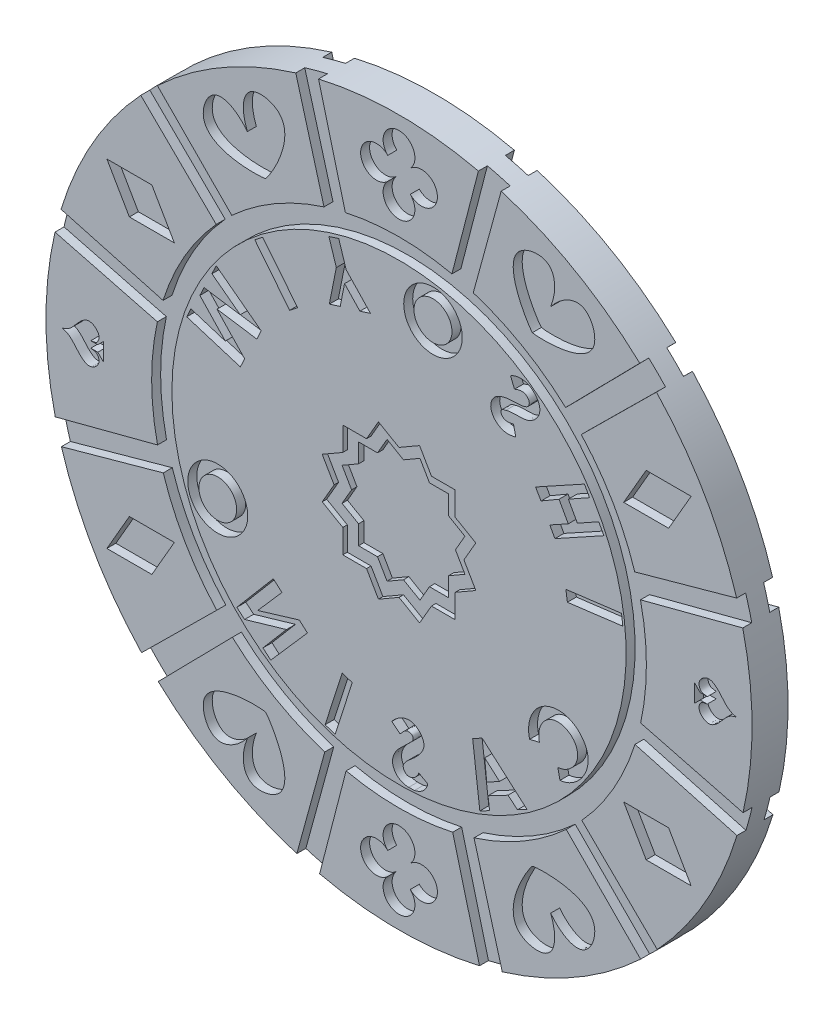
SolidWorks part; units mm, degrees
ref_plane "Front Plane" through (0, 0, 0) normal (0, 0, 1) x (1, 0, 0)
ref_plane "Top Plane" through (0, 0, 0) normal (0, 1, 0) x (1, 0, 0)
ref_plane "Right Plane" through (0, 0, 0) normal (1, 0, 0) x (0, 0, -1)
sketch "Sketch1" plane through (0, 0, 0) normal (0, 0, 1) x (1, 0, 0)
  circle A0 centre (0, 0) radius 19.939
  dimension "D1" = 39.878
extrude "Boss-Extrude1" add sketch "Sketch1" along normal blind 2.032
sketch "Sketch2" plane through (0, 0, 0) normal (0, 0, -1) x (-1, 0, 0)
  line L0 (0, 19.05) -> (0, 18.269) construction
  line L1 (-19.05, 0) -> (19.05, 0) construction
  line L2 (-16.4978, 9.525) -> (16.4978, -9.525) construction
  line L3 (-16.4978, -9.525) -> (16.4978, 9.525) construction
  line L12 (-2.5249, 16.999) -> (-1.27, 16.999) construction
  line L13 (-0.372, 16.999) -> (0, 16.999) construction
  line L14 (0, 17.3709) -> (0, 16.627) construction
  line L15 (-9.525, 16.4978) -> (9.525, -16.4978) construction
  line L16 (0, 14.8309) -> (0, -19.05) construction
  line L17 (-9.525, -16.4978) -> (9.525, 16.4978) construction
  line L18 (-16.4978, 9.525) -> (-15.2278, 7.3253)
  line L19 (-15.2278, 7.3253) -> (-12.6878, 7.3253)
  line L20 (-12.6878, 7.3253) -> (-13.9578, 9.525)
  line L21 (-13.9578, 9.525) -> (-16.4978, 9.525)
  line L22 (-18.7055, 0.0763) -> (-18.7307, 0)
  line L24 (-17.4086, 0.1821) -> (-17.0116, 0.1821)
  line L29 (12.6878, 7.3253) -> (13.9578, 9.525)
  line L30 (15.2278, 7.3253) -> (12.6878, 7.3253)
  line L31 (16.4978, 9.525) -> (15.2278, 7.3253)
  line L32 (13.9578, 9.525) -> (16.4978, 9.525)
  line L33 (15.2278, -7.3253) -> (12.6878, -7.3253)
  line L34 (16.4978, -9.525) -> (15.2278, -7.3253)
  line L35 (13.9578, -9.525) -> (16.4978, -9.525)
  line L36 (12.6878, -7.3253) -> (13.9578, -9.525)
  line L37 (-12.6878, -7.3253) -> (-13.9578, -9.525)
  line L38 (-15.2278, -7.3253) -> (-12.6878, -7.3253)
  line L39 (-16.4978, -9.525) -> (-15.2278, -7.3253)
  line L40 (-13.9578, -9.525) -> (-16.4978, -9.525)
  line L41 (-17.0116, 0.1821) -> (-16.6763, 0.5174)
  line L42 (-16.6763, 0.5174) -> (-16.6763, -0.5174)
  line L43 (-17.0116, -0.1821) -> (-16.6763, -0.5174)
  line L44 (-17.4086, -0.1821) -> (-17.0116, -0.1821)
  line L45 (17.0116, 0.1821) -> (16.6763, 0.5174)
  line L46 (17.4086, 0.1821) -> (17.0116, 0.1821)
  line L47 (17.4086, -0.1821) -> (17.0116, -0.1821)
  line L48 (17.0116, -0.1821) -> (16.6763, -0.5174)
  line L49 (16.6763, 0.5174) -> (16.6763, -0.5174)
  circle A1 centre (0, 0) radius 12.7
  arc A4 (-0.635, 17.634) -> (-0.635, 16.364) centre (-1.27, 16.999) ccw
  arc A5 (0.635, 17.634) -> (-0.635, 17.634) centre (0, 18.269) ccw
  arc A6 (0.635, 16.364) -> (0.635, 17.634) centre (1.27, 16.999) ccw
  arc A7 (-0.635, 16.364) -> (0.635, 16.364) centre (0, 15.729) ccw
  arc A8 (0.635, -17.634) -> (-0.635, -17.634) centre (0, -18.269) cw
  arc A9 (0.635, -16.364) -> (0.635, -17.634) centre (1.27, -16.999) cw
  arc A10 (-0.635, -16.364) -> (0.635, -16.364) centre (0, -15.729) cw
  arc A11 (-0.635, -17.634) -> (-0.635, -16.364) centre (-1.27, -16.999) cw
  spline S0 degree 3 poles (-8.5627, 14.8309) (-9.1367, 15.5617) (-10.5729, 16.2747) (-11.874, 12.8398) (-7.9104, 12.9447) (-7.5331, 13.0477) knots 0 0 0 0 0.213982 0.428157 1 1 1 1
  spline S1 degree 3 poles (-8.5627, 14.8309) (-8.9085, 15.6935) (-8.8078, 17.2938) (-5.1826, 16.7031) (-7.2552, 13.3229) (-7.5331, 13.0477) knots 0 0 0 0 0.213982 0.428157 1 1 1 1
  spline S2 degree 3 poles (-19.05, 0) (-18.5032, 0.0976) (-18.2648, 0.6842) (-17.5658, 1.1681) (-17.1191, 0.9874) (-16.8707, 0.6317) (-17.0509, 0.1906) (-17.2855, 0.2112) (-17.4086, 0.1821) knots 0 0 0 0 0.410966 0.558538 0.671524 0.797339 0.904759 1 1 1 1
  spline S3 degree 3 poles (-19.05, 0) (-18.5032, -0.0976) (-18.2648, -0.6842) (-17.5658, -1.1681) (-17.1191, -0.9874) (-16.8707, -0.6317) (-17.0509, -0.1906) (-17.2855, -0.2112) (-17.4086, -0.1821) knots 0 0 0 0 0.410966 0.558538 0.671524 0.797339 0.904759 1 1 1 1
  spline S4 degree 3 poles (19.05, 0) (18.5032, 0.0976) (18.2648, 0.6842) (17.5658, 1.1681) (17.1191, 0.9874) (16.8707, 0.6317) (17.0509, 0.1906) (17.2855, 0.2112) (17.4086, 0.1821) knots 0 0 0 0 0.410966 0.558538 0.671524 0.797339 0.904759 1 1 1 1
  spline S5 degree 3 poles (19.05, 0) (18.5032, -0.0976) (18.2648, -0.6842) (17.5658, -1.1681) (17.1191, -0.9874) (16.8707, -0.6317) (17.0509, -0.1906) (17.2855, -0.2112) (17.4086, -0.1821) knots 0 0 0 0 0.410966 0.558538 0.671524 0.797339 0.904759 1 1 1 1
  spline S10 degree 3 poles (8.5627, 14.8309) (9.1367, 15.5617) (10.5729, 16.2747) (11.874, 12.8398) (7.9104, 12.9447) (7.5331, 13.0477) knots 0 0 0 0 0.213982 0.428157 1 1 1 1
  spline S11 degree 3 poles (8.5627, 14.8309) (8.9085, 15.6935) (8.8078, 17.2938) (5.1826, 16.7031) (7.2552, 13.3229) (7.5331, 13.0477) knots 0 0 0 0 0.213982 0.428157 1 1 1 1
  spline S12 degree 3 poles (8.5627, -14.8309) (8.9085, -15.6935) (8.8078, -17.2938) (5.1826, -16.7031) (7.2552, -13.3229) (7.5331, -13.0477) knots 0 0 0 0 0.213982 0.428157 1 1 1 1
  spline S13 degree 3 poles (8.5627, -14.8309) (9.1367, -15.5617) (10.5729, -16.2747) (11.874, -12.8398) (7.9104, -12.9447) (7.5331, -13.0477) knots 0 0 0 0 0.213982 0.428157 1 1 1 1
  spline S14 degree 3 poles (-8.5627, -14.8309) (-9.1367, -15.5617) (-10.5729, -16.2747) (-11.874, -12.8398) (-7.9104, -12.9447) (-7.5331, -13.0477) knots 0 0 0 0 0.213982 0.428157 1 1 1 1
  spline S15 degree 3 poles (-8.5627, -14.8309) (-8.9085, -15.6935) (-8.8078, -17.2938) (-5.1826, -16.7031) (-7.2552, -13.3229) (-7.5331, -13.0477) knots 0 0 0 0 0.213982 0.428157 1 1 1 1
  text T0 "<b> MIYOSHI CASINO</b>"
  point P11 (0, 0)
  point P14 (0, 0)
  point P30 (0, 0)
  point P35 (0, 0)
  point P53 (-16.6763, 0)
  point P65 (-17.8684, 0)
  point P80 (17.8684, 0)
  dimension "D1" = 25.4
  dimension "D8" = 30
  dimension "D9" = 30
  dimension "D2" = 30
  dimension "D3" = 30
  dimension "D4" = 19.05
  dimension "D5" = 19.05
  dimension "D6" = 19.05
  dimension "D7" = 2.54
extrude "Cut-Extrude1" cut sketch "Sketch2" against normal blind 0.508
sketch "Sketch3" plane through (0, 0, 0) normal (0, 0, -1) x (-1, 0, 0)
  line L0 (-7.2401, -10.4341) -> (-6.6912, -10.7074)
  line L1 (-6.6912, -10.7074) -> (-6.1553, -10.2652)
  line L2 (-6.1553, -10.2652) -> (-5.0278, -10.8578)
  line L3 (-5.0278, -10.8578) -> (-5.1144, -11.5417)
  line L4 (-5.1144, -11.5417) -> (-4.5639, -11.831)
  line L5 (-4.5639, -11.831) -> (-4.1584, -8.4872)
  line L6 (-4.1584, -8.4872) -> (-4.6966, -8.2044)
  line L7 (-4.6966, -8.2044) -> (-7.2401, -10.4341)
  line L8 (-4.8391, -9.0944) -> (-5.6779, -9.8298)
  line L9 (-5.6779, -9.8298) -> (-4.954, -10.2307)
  line L10 (-4.954, -10.2307) -> (-4.8391, -9.0944)
  line L11 (-8.9704, -7.4953) -> (-9.0904, -8.0718)
  line L12 (-7.9319, -6.7945) -> (-7.3784, -6.9182)
  line L13 (2.6414, -9.1541) -> (3.2081, -8.9773)
  line L14 (3.2081, -8.9773) -> (4.1732, -11.9832)
  line L15 (4.1732, -11.9832) -> (3.603, -12.1662)
  line L16 (3.603, -12.1662) -> (2.6414, -9.1541)
  line L17 (7.2439, -10.3617) -> (5.1705, -7.9937)
  line L18 (5.1705, -7.9937) -> (5.6316, -7.59)
  line L19 (5.6316, -7.59) -> (7.9806, -8.2989)
  line L20 (7.9806, -8.2989) -> (6.6099, -6.7335)
  line L21 (6.6099, -6.7335) -> (7.0983, -6.3058)
  line L22 (7.0983, -6.3058) -> (9.1591, -8.733)
  line L23 (9.1591, -8.733) -> (8.7187, -9.107)
  line L24 (8.7187, -9.107) -> (6.3572, -8.4187)
  line L25 (6.3572, -8.4187) -> (7.6816, -9.9785)
  line L26 (7.6816, -9.9785) -> (7.2439, -10.3617)
  line L27 (0.4083, -9.9381) -> (-0.0561, -10.3143)
  line L28 (-1.6261, -11.9832) -> (-1.1106, -11.6888)
  line L29 (-9.4245, 1.4385) -> (-9.5089, 0.848)
  line L30 (-9.5089, 0.848) -> (-12.6389, 1.2446)
  line L31 (-12.6389, 1.2446) -> (-12.5666, 1.8359)
  line L32 (-12.5666, 1.8359) -> (-9.4245, 1.4385)
  line L33 (-11.5721, 5.1356) -> (-8.8054, 3.6094)
  line L34 (-8.8054, 3.6094) -> (-8.5165, 4.1331)
  line L35 (-8.5165, 4.1331) -> (-9.5573, 4.7071)
  line L36 (-9.5573, 4.7071) -> (-9.0369, 5.6506)
  line L37 (-9.0369, 5.6506) -> (-8.0202, 5.0582)
  line L38 (-8.0202, 5.0582) -> (-7.7116, 5.5877)
  line L39 (-7.7116, 5.5877) -> (-10.475, 7.1119)
  line L40 (-10.475, 7.1119) -> (-10.7629, 6.5899)
  line L41 (-10.7629, 6.5899) -> (-9.5637, 5.9193)
  line L42 (-9.5637, 5.9193) -> (-10.072, 4.9979)
  line L43 (-10.072, 4.9979) -> (-11.2781, 5.6687)
  line L44 (-11.2781, 5.6687) -> (-11.5721, 5.1356)
  line L45 (3.3201, 8.902) -> (3.936, 8.7065)
  line L46 (3.936, 8.7065) -> (3.541, 10.6905)
  line L47 (3.541, 10.6905) -> (3.9582, 12.0045)
  line L48 (3.9582, 12.0045) -> (3.4032, 12.1807)
  line L49 (3.4032, 12.1807) -> (2.9861, 10.8667)
  line L50 (2.9861, 10.8667) -> (1.612, 9.4154)
  line L51 (1.612, 9.4154) -> (2.2086, 9.226)
  line L52 (2.2086, 9.226) -> (3.075, 10.1411)
  line L53 (3.075, 10.1411) -> (3.3201, 8.902)
  line L54 (5.7213, 7.6355) -> (6.1766, 7.284)
  line L55 (6.1766, 7.284) -> (8.1426, 9.7462)
  line L56 (8.1426, 9.7462) -> (7.7018, 10.0982)
  line L57 (7.7018, 10.0982) -> (5.7213, 7.6355)
  line L58 (11.7495, 4.5708) -> (11.9861, 4.0617)
  line L59 (11.9861, 4.0617) -> (8.9602, 3.1224)
  line L60 (8.9602, 3.1224) -> (8.7187, 3.6419)
  line L61 (8.7187, 3.6419) -> (10.2781, 5.2889)
  line L62 (10.2781, 5.2889) -> (8.028, 4.9509)
  line L63 (8.028, 4.9509) -> (7.7835, 5.4768)
  line L64 (7.7835, 5.4768) -> (10.3258, 7.3937)
  line L65 (10.3258, 7.3937) -> (10.5661, 6.8768)
  line L66 (10.5661, 6.8768) -> (8.9673, 5.6713)
  line L67 (8.9673, 5.6713) -> (11.0131, 5.9786)
  line L68 (11.0131, 5.9786) -> (11.2463, 5.4768)
  line L69 (11.2463, 5.4768) -> (9.8112, 3.9611)
  line L70 (9.8112, 3.9611) -> (11.7495, 4.5708)
  line L71 (-6.5922, 7.4641) -> (-6.4686, 8.0429)
  line L72 (-6.5219, 9.7751) -> (-6.2992, 10.3174)
  circle A0 centre (0, 0) radius 12.7
  circle A1 centre (10.2365, -3.955) radius 1.0663
  circle A2 centre (10.2365, -3.955) radius 1.6933
  circle A3 centre (-1.9188, 10.8242) radius 1.0731
  circle A4 centre (-1.9188, 10.8242) radius 1.6532
  spline S0 degree 3 poles (-8.9704, -7.4953) (-9.5179, -7.4725) (-10.2698, -6.7584) (-9.9232, -5.5556) (-9.0667, -5.1524) (-8.3718, -5.4157) (-8.0059, -5.8305) (-7.8698, -6.3314) (-7.9006, -6.6665) (-7.9319, -6.7945) knots 0 0 0 0 0.300665 0.426683 0.634982 0.725339 0.818543 0.927548 1 1 1 1
  spline S1 degree 3 poles (-9.0904, -8.0718) (-9.5973, -8.0222) (-10.3866, -7.504) (-10.8334, -6.2358) (-10.3239, -5.1572) (-9.2654, -4.5286) (-7.6032, -4.9297) (-7.1908, -6.2373) (-7.3784, -6.9182) knots 0 0 0 0 0.179528 0.326335 0.445822 0.586433 0.743647 1 1 1 1
  spline S2 degree 3 poles (-1.1106, -11.6888) (-1.0863, -11.9226) (-0.5177, -12.403) (-0.1845, -11.849) (-0.3434, -11.5291) (-0.704, -11.2216) (-1.1619, -10.826) (-1.491, -10.2485) (-1.2542, -9.683) (-0.5395, -9.1553) (0.1711, -9.6278) (0.4083, -9.9381) knots 0 0 0 0 0.153765 0.224336 0.249997 0.337815 0.471409 0.579286 0.655102 0.77698 1 1 1 1
  spline S3 degree 3 poles (-0.0561, -10.3143) (-0.1845, -10.2168) (-0.3172, -9.9019) (-0.8207, -9.9914) (-0.8029, -10.287) (-0.6869, -10.3924) (-0.5605, -10.5284) (-0.3118, -10.7598) (0.1347, -11.142) (0.5099, -11.8517) (0.0969, -12.557) (-0.7945, -12.8054) (-1.4931, -12.5257) (-1.6261, -11.9832) knots 0 0 0 0 0.088514 0.149178 0.191359 0.208149 0.230554 0.28825 0.38443 0.542473 0.651548 0.759918 1 1 1 1
  spline S4 degree 3 poles (-6.5219, 9.7751) (-6.6664, 9.8431) (-6.8776, 9.9064) (-7.1396, 9.8509) (-7.2442, 9.7608) (-7.3224, 9.6631) (-7.3668, 9.5503) (-7.3482, 9.4277) (-7.2954, 9.3004) (-7.1488, 9.2237) (-6.8893, 9.1617) (-6.2634, 9.1564) (-5.3842, 9.0513) (-5.1309, 8.3069) (-5.3141, 7.7253) (-5.8527, 7.3761) (-6.3342, 7.4103) (-6.5213, 7.449) (-6.5922, 7.4641) knots 0 0 0 0 0.085958 0.111215 0.138605 0.157059 0.177812 0.200582 0.221425 0.248361 0.283662 0.363274 0.588263 0.668484 0.745865 0.89907 0.961119 1 1 1 1
  spline S5 degree 3 poles (-6.4686, 8.0429) (-6.3085, 8.0056) (-5.8617, 7.8712) (-5.6034, 8.44) (-6.0264, 8.4941) knots 0 0 0 0 0.448974 1 1 1 1
  spline S6 degree 3 poles (-6.0264, 8.4941) (-6.4239, 8.6279) (-7.1458, 8.4252) (-7.8321, 8.961) (-8.0289, 9.5627) (-7.7616, 10.0936) (-7.1593, 10.5442) (-6.5861, 10.5085) (-6.2992, 10.3174) knots 0 0 0 0 0.27712 0.430763 0.516832 0.672725 0.776938 1 1 1 1
  dimension "D1" = 25.4
extrude "Cut-Extrude2" cut sketch "Sketch3" against normal blind 0.508 contours S1 L11 S0 L12 | L6 L7 L0 L1 L2 L3 L4 L5 L10 L9 L8 | S3 L27 S2 L28 A0 | L16 L15 L14 L13 | L26 L25 L24 L23 L22 L21 L20 L19 L18 L17 | A2 A1 | L43 L44 L33 L34 L35 L36 L37 L38 L39 L40 L41 L42 | A4 A3 | L52 L53 L45 L46 L47 L48 L49 L50 L51 | L56 L57 L54 L55 | L32 L29 L30 L31 | S5 S6 L72 S4 L71 | L62 L63 L64 L65 L66 L67 L68 L69 L70 L58 L59 L60 L61
sketch "Sketch5" plane through (0, 0, 0) normal (0, 0, -1) x (-1, 0, 0)
  line L0 (-19.939, 0) -> (-12.7, 0) construction
  line L19 (13.97, 0) -> (19.939, 0) construction
  line L26 (-19.2935, 5.8932) -> (-13.3124, 4.2357)
  line L27 (-19.6408, 4.6053) -> (-13.6372, 3.0311)
  line L28 (-14.7068, 13.8087) -> (-10.2946, 9.4436)
  line L29 (-13.7621, 14.7504) -> (-9.411, 10.3244)
  line L30 (-5.8321, 19.3121) -> (-4.1935, 13.3257)
  line L31 (-4.5431, 19.6553) -> (-2.988, 13.6467)
  line L32 (4.6053, 19.6408) -> (3.0311, 13.6372)
  line L33 (5.8932, 19.2935) -> (4.2357, 13.3124)
  line L34 (13.8087, 14.7068) -> (9.4436, 10.2946)
  line L35 (14.7504, 13.7621) -> (10.3244, 9.411)
  line L36 (19.3121, 5.8321) -> (13.3257, 4.1935)
  line L37 (19.6553, 4.5431) -> (13.6467, 2.988)
  line L38 (19.6408, -4.6053) -> (13.6372, -3.0311)
  line L39 (19.2935, -5.8932) -> (13.3124, -4.2357)
  line L40 (14.7068, -13.8087) -> (10.2946, -9.4436)
  line L41 (13.7621, -14.7504) -> (9.411, -10.3244)
  line L42 (5.8321, -19.3121) -> (4.1935, -13.3257)
  line L43 (4.5431, -19.6553) -> (2.988, -13.6467)
  line L44 (-4.6053, -19.6408) -> (-3.0311, -13.6372)
  line L45 (-5.8932, -19.2935) -> (-4.2357, -13.3124)
  line L46 (-13.8087, -14.7068) -> (-9.4436, -10.2946)
  line L47 (-14.7504, -13.7621) -> (-10.3244, -9.411)
  line L48 (-19.3121, -5.8321) -> (-13.3257, -4.1935)
  line L49 (-19.6553, -4.5431) -> (-13.6467, -2.988)
  circle A0 centre (0, 0) radius 12.7
  circle A2 centre (0, 0) radius 20.1735
  arc A3 (-13.6372, 3.0311) -> (-13.6467, -2.988) centre (0, 0) ccw
  arc A4 (-13.3257, -4.1935) -> (-10.3244, -9.411) centre (0, 0) ccw
  arc A5 (-10.2946, 9.4436) -> (-13.3124, 4.2357) centre (0, 0) ccw
  arc A6 (-4.1935, 13.3257) -> (-9.411, 10.3244) centre (0, 0) ccw
  arc A7 (3.0311, 13.6372) -> (-2.988, 13.6467) centre (0, 0) ccw
  arc A8 (9.4436, 10.2946) -> (4.2357, 13.3124) centre (0, 0) ccw
  arc A9 (13.3257, 4.1935) -> (10.3244, 9.411) centre (0, 0) ccw
  arc A10 (13.6372, -3.0311) -> (13.6467, 2.988) centre (0, 0) ccw
  arc A11 (-9.4436, -10.2946) -> (-4.2357, -13.3124) centre (0, 0) ccw
  arc A12 (-3.0311, -13.6372) -> (2.988, -13.6467) centre (0, 0) ccw
  arc A13 (4.1935, -13.3257) -> (9.411, -10.3244) centre (0, 0) ccw
  arc A14 (10.2946, -9.4436) -> (13.3124, -4.2357) centre (0, 0) ccw
  circle A15 centre (0, 0) radius 12.827
  point P30 (0, 0)
  point P84 (0, 0)
  dimension "D3" = 25.4
  dimension "D2" = 27.94
  dimension "D1" = 25.654
  dimension "D7" = 12
extrude "Cut-Extrude3" cut sketch "Sketch5" against normal blind 0.508 contours L40 A14 L39 A2 L38 A10 L37 L36 A9 L35 L34 A8 L33 L32 A7 L31 L30 A6 L29 L28 A5 L26 L27 A3 L49 L48 A4 L47 L46 A11 L45 L44 A12 L43 L42 A13 L41 A15
sketch "Sketch7" plane through (0, 0, 0) normal (0, 0, -1) x (-1, 0, 0)
  line L42 (1.1621, 4.3371) -> (-4.3371, 1.1621)
  line L43 (-3.175, 3.175) -> (3.175, 3.175)
  line L64 (-3.175, 3.175) -> (-3.175, -3.175)
  line L65 (-3.175, -3.175) -> (3.175, -3.175)
  line L66 (3.175, 3.175) -> (3.175, -3.175)
  line L67 (-3.175, 3.175) -> (3.175, -3.175) construction
  line L68 (-3.175, -3.175) -> (3.175, 3.175) construction
  line L69 (1.1621, 4.3371) -> (4.3371, -1.1621)
  line L70 (4.3371, -1.1621) -> (-1.1621, -4.3371)
  line L71 (-4.3371, 1.1621) -> (-1.1621, -4.3371)
  line L72 (4.3371, 1.1621) -> (-1.1621, 4.3371)
  line L73 (4.3371, 1.1621) -> (1.1621, -4.3371)
  line L74 (1.1621, -4.3371) -> (-4.3371, -1.1621)
  line L75 (-1.1621, 4.3371) -> (-4.3371, -1.1621)
  line L76 (3.175, -3.175) -> (3.175, 3.175)
  line L77 (3.175, -3.175) -> (-3.175, -3.175)
  line L78 (-3.175, -3.175) -> (-3.175, 3.175)
  line L79 (3.175, 3.175) -> (-3.175, 3.175)
  line L80 (-1.1621, -4.3371) -> (4.3371, -1.1621)
  line L81 (-1.1621, -4.3371) -> (-4.3371, 1.1621)
  line L82 (-4.3371, 1.1621) -> (1.1621, 4.3371)
  line L83 (4.3371, -1.1621) -> (1.1621, 4.3371)
  line L84 (-4.3371, -1.1621) -> (1.1621, -4.3371)
  line L85 (-4.3371, -1.1621) -> (-1.1621, 4.3371)
  line L86 (-1.1621, 4.3371) -> (4.3371, 1.1621)
  line L87 (1.1621, -4.3371) -> (4.3371, 1.1621)
  point P0 (0, 0)
  point P29 (0, 0)
  dimension "D1" = 6.35
  dimension "D2" = 6.35
  dimension "D3" = 6
extrude "Cut-Extrude10" cut sketch "Sketch7" against normal blind 0.254 contours L71 L75 L74 L64 | L75 L64 L42 L71 | L75 L43 L64 L42 | L72 L75 L43 L42 | L72 L43 L69 L42 | L72 L66 L43 L69 | L73 L72 L66 L69 | L69 L73 L66 L70 | L70 L73 L65 L66 | L74 L73 L65 L70 | L70 L74 L65 L71 | L71 L74 L64 L65 | L74 L71 L64 | L75 L42 L64 | L64 L75 L71 | L42 L75 L64 L71 L74 L65 L70 L73 L66 L69 L72 L43 | L66 L73 L70 | L73 L70 L65 | L65 L74 L71 | L43 L72 L42 | L43 L75 L42 | L72 L69 L43 | L66 L72 L69 | L73 L69 L66 | L74 L70 L65
sketch "Sketch8" plane through (0, 0, 0.254) normal (0, 0, -1) x (-1, 0, 0)
  line L0 (0.9297, 3.4697) -> (-3.4697, 0.9297)
  line L1 (-2.54, 2.54) -> (2.54, 2.54)
  line L2 (-2.54, 2.54) -> (-2.54, -2.54)
  line L3 (-2.54, -2.54) -> (2.54, -2.54)
  line L4 (2.54, 2.54) -> (2.54, -2.54)
  line L5 (-2.54, 2.54) -> (2.54, -2.54) construction
  line L6 (-2.54, -2.54) -> (2.54, 2.54) construction
  line L7 (0.9297, 3.4697) -> (3.4697, -0.9297)
  line L8 (3.4697, -0.9297) -> (-0.9297, -3.4697)
  line L9 (-3.4697, 0.9297) -> (-0.9297, -3.4697)
  line L10 (3.4697, 0.9297) -> (-0.9297, 3.4697)
  line L11 (3.4697, 0.9297) -> (0.9297, -3.4697)
  line L12 (0.9297, -3.4697) -> (-3.4697, -0.9297)
  line L13 (-0.9297, 3.4697) -> (-3.4697, -0.9297)
  line L14 (2.54, -2.54) -> (2.54, 2.54)
  line L15 (2.54, -2.54) -> (-2.54, -2.54)
  line L16 (-2.54, -2.54) -> (-2.54, 2.54)
  line L17 (2.54, 2.54) -> (-2.54, 2.54)
  line L18 (-0.9297, -3.4697) -> (3.4697, -0.9297)
  line L19 (-0.9297, -3.4697) -> (-3.4697, 0.9297)
  line L20 (-3.4697, 0.9297) -> (0.9297, 3.4697)
  line L21 (3.4697, -0.9297) -> (0.9297, 3.4697)
  line L22 (-3.4697, -0.9297) -> (0.9297, -3.4697)
  line L23 (-3.4697, -0.9297) -> (-0.9297, 3.4697)
  line L24 (-0.9297, 3.4697) -> (3.4697, 0.9297)
  line L25 (0.9297, -3.4697) -> (3.4697, 0.9297)
  point P0 (0, 0)
  point P29 (0, 0)
  dimension "D1" = 5.08
  dimension "D2" = 5.08
extrude "Cut-Extrude11" cut sketch "Sketch8" against normal blind 0.3048 contours L13 L12 L11 L10 | L0 L9 L8 L7 | L1 L4 L3 L2
sketch "Sketch9" plane through (0, 0, 0.5588) normal (0, 0, -1) x (-1, 0, 0)
  line L0 (0.6973, 2.6023) -> (-2.6023, 0.6973)
  line L1 (-1.905, 1.905) -> (1.905, 1.905)
  line L2 (-1.905, 1.905) -> (-1.905, -1.905)
  line L3 (-1.905, -1.905) -> (1.905, -1.905)
  line L4 (1.905, 1.905) -> (1.905, -1.905)
  line L5 (-1.905, 1.905) -> (1.905, -1.905) construction
  line L6 (-1.905, -1.905) -> (1.905, 1.905) construction
  line L7 (0.6973, 2.6023) -> (2.6023, -0.6973)
  line L8 (2.6023, -0.6973) -> (-0.6973, -2.6023)
  line L9 (-2.6023, 0.6973) -> (-0.6973, -2.6023)
  line L10 (2.6023, 0.6973) -> (-0.6973, 2.6023)
  line L11 (2.6023, 0.6973) -> (0.6973, -2.6023)
  line L12 (0.6973, -2.6023) -> (-2.6023, -0.6973)
  line L13 (-0.6973, 2.6023) -> (-2.6023, -0.6973)
  line L14 (1.905, -1.905) -> (1.905, 1.905)
  line L15 (1.905, -1.905) -> (-1.905, -1.905)
  line L16 (-1.905, -1.905) -> (-1.905, 1.905)
  line L17 (1.905, 1.905) -> (-1.905, 1.905)
  line L18 (-0.6973, -2.6023) -> (2.6023, -0.6973)
  line L19 (-0.6973, -2.6023) -> (-2.6023, 0.6973)
  line L20 (-2.6023, 0.6973) -> (0.6973, 2.6023)
  line L21 (2.6023, -0.6973) -> (0.6973, 2.6023)
  line L22 (-2.6023, -0.6973) -> (0.6973, -2.6023)
  line L23 (-2.6023, -0.6973) -> (-0.6973, 2.6023)
  line L24 (-0.6973, 2.6023) -> (2.6023, 0.6973)
  line L25 (0.6973, -2.6023) -> (2.6023, 0.6973)
  point P0 (0, 0)
  point P28 (0, 0)
  dimension "D1" = 3.81
  dimension "D2" = 3.81
ref_plane "Plane1" through (0, 0, 1.016) normal (0, 0, -1) x (-1, 0, 0)
mirror "Mirror3" about plane through (0, 0, 1.016) normal (0, 0, -1) of "Cut-Extrude11", "Cut-Extrude10", "Cut-Extrude3", "Cut-Extrude2", "Cut-Extrude1"
